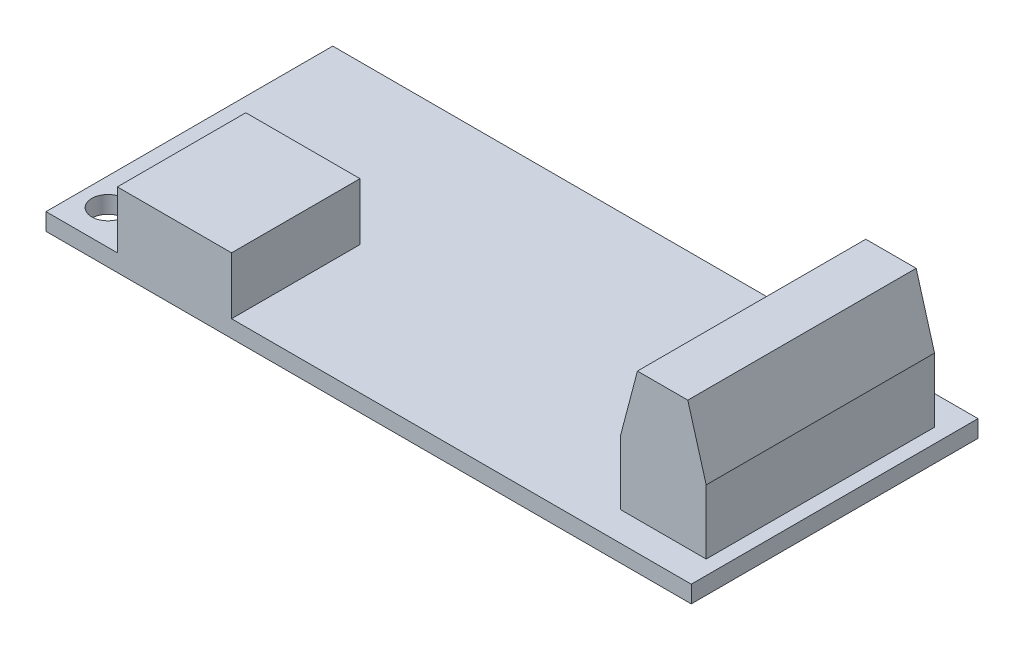
SolidWorks part; units mm, degrees
ref_plane "Front Plane" through (0, 0, 0) normal (0, 0, 1) x (1, 0, 0)
ref_plane "Top Plane" through (0, 0, 0) normal (0, 1, 0) x (1, 0, 0)
ref_plane "Right Plane" through (0, 0, 0) normal (1, 0, 0) x (0, 0, -1)
sketch "Sketch1" plane through (0, 0, 0) normal (0, 1, 0) x (1, 0, 0)
  line L1 (-22.605, 10.045) -> (22.605, 10.045)
  line L2 (-22.605, 10.045) -> (-22.605, -10.045)
  line L3 (-22.605, -10.045) -> (22.605, -10.045)
  line L4 (22.605, 10.045) -> (22.605, -10.045)
  line L5 (-22.605, 10.045) -> (22.605, -10.045) construction
  line L6 (-22.605, -10.045) -> (22.605, 10.045) construction
  circle A0 centre (11.835, 7.785) radius 1.13
  circle A1 centre (-20.675, -7.635) radius 1.13
  point P4 (0, 0)
  dimension "D3" = 2.26
  dimension "D4" = 2.26
  dimension "D1" = 45.21
  dimension "D2" = 20.09
  dimension "D5" = 1.93
  dimension "D6" = 32.51
  dimension "D7" = 15.42
  dimension "D8" = 17.68
extrude "Boss-Extrude1" add sketch "Sketch1" along normal blind 1.2
sketch "Sketch2" plane through (0, 1.2, 0) normal (0, 1, 0) x (1, 0, 0)
  line L0 (22.605, -10.045) -> (22.605, 10.045) construction
  line L1 (15.605, 8) -> (21.605, 8)
  line L2 (15.605, 8) -> (15.605, -8)
  line L3 (15.605, -8) -> (21.605, -8)
  line L4 (21.605, 8) -> (21.605, -8)
  line L5 (15.605, 8) -> (21.605, -8) construction
  line L6 (15.605, -8) -> (21.605, 8) construction
  point P4 (18.605, 0)
  point P5 (21.605, 0)
  point P8 (22.605, 0)
  dimension "D1" = 16
  dimension "D2" = 6
  dimension "D3" = 1
extrude "Boss-Extrude3" add sketch "Sketch2" along normal blind 9
sketch "Sketch4" plane through (0, 0, 8) normal (0, 0, 1) x (1, 0, 0)
  line L0 (15.605, 5.7) -> (16.7882, 10.2)
  line L1 (15.605, 10.2) -> (21.605, 10.2) construction
  line L2 (15.605, 10.2) -> (15.605, 1.2) construction
  line L3 (20.3174, 10.2) -> (21.605, 5.7)
  line L4 (21.605, 10.2) -> (21.605, 1.2) construction
  line L5 (20.3174, 10.2) -> (21.605, 10.2)
  line L6 (21.605, 10.2) -> (21.605, 5.7)
  line L7 (16.7882, 10.2) -> (15.605, 10.2)
  line L8 (15.605, 10.2) -> (15.605, 5.7)
extrude "Cut-Extrude1" cut sketch "Sketch4" against normal up to next
sketch "Sketch5" plane through (0, 1.2, 0) normal (0, 1, 0) x (1, 0, 0)
  line L0 (-22.605, 10.045) -> (-22.605, -10.045) construction
  line L1 (-17.605, -1.045) -> (-9.605, -1.045)
  line L2 (-17.605, -1.045) -> (-17.605, -10.045)
  line L3 (-17.605, -10.045) -> (-9.605, -10.045)
  line L4 (-9.605, -1.045) -> (-9.605, -10.045)
  line L5 (-17.605, -1.045) -> (-9.605, -10.045) construction
  line L6 (-17.605, -10.045) -> (-9.605, -1.045) construction
  point P4 (-13.605, -5.545)
  dimension "D1" = 8
  dimension "D2" = 9
  dimension "D3" = 5
extrude "Boss-Extrude5" add sketch "Sketch5" along normal blind 4
